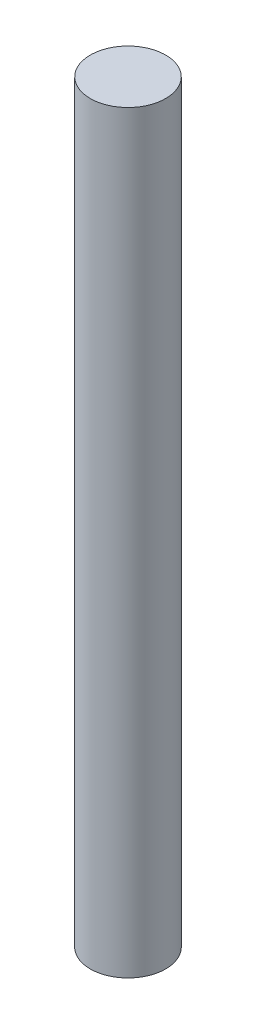
SolidWorks part; units mm, degrees
ref_plane "Front Plane" through (0, 0, 0) normal (0, 0, 1) x (1, 0, 0)
ref_plane "Top Plane" through (0, 0, 0) normal (0, 1, 0) x (1, 0, 0)
ref_plane "Right Plane" through (0, 0, 0) normal (1, 0, 0) x (0, 0, -1)
sketch "Sketch1" plane through (0, 0, 0) normal (0, 1, 0) x (1, 0, 0)
  circle A0 centre (0, 0) radius 0.5
  dimension "D1" = 1
extrude "Boss-Extrude1" add sketch "Sketch1" along normal mid plane 10
